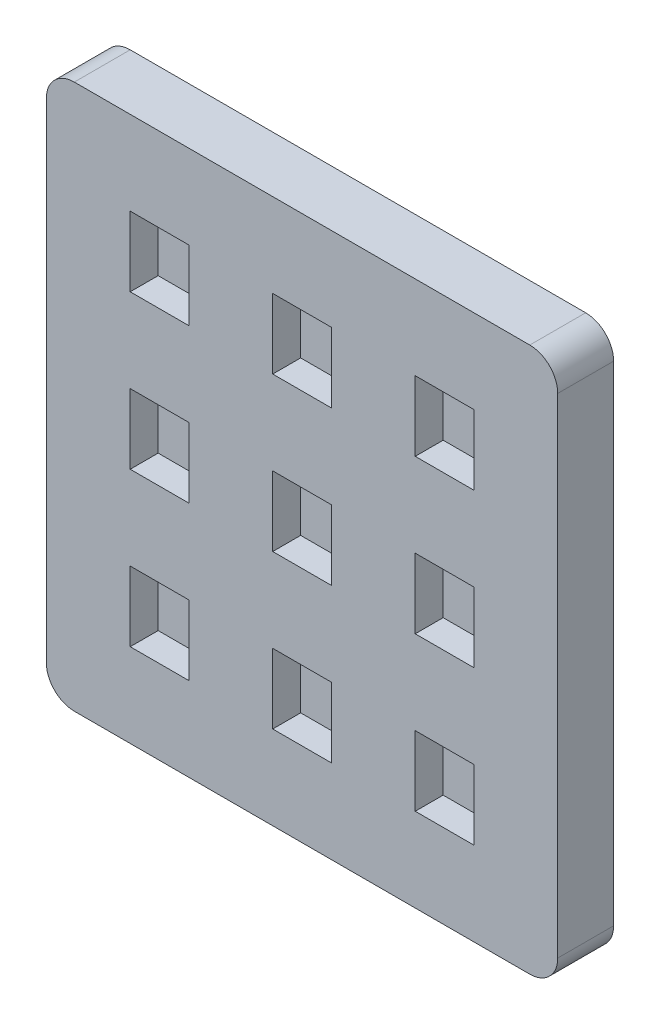
SolidWorks part; units mm, degrees
ref_plane "Front Plane" through (0, 0, 0) normal (0, 0, 1) x (1, 0, 0)
ref_plane "Top Plane" through (0, 0, 0) normal (0, 1, 0) x (1, 0, 0)
ref_plane "Right Plane" through (0, 0, 0) normal (1, 0, 0) x (0, 0, -1)
sketch "Sketch1" plane through (0, 0, 0) normal (0, 0, 1) x (1, 0, 0)
  line L1 (0, 0) -> (183, 0)
  line L2 (0, 0) -> (0, 195)
  line L3 (0, 195) -> (183, 195)
  line L4 (183, 0) -> (183, 195)
extrude "Boss-Extrude2" add sketch "Sketch1" along normal blind 20
sketch "Sketch3" plane through (0, 0, 20) normal (0, 0, 1) x (1, 0, 0)
  line L2 (30, 110) -> (51, 110)
  line L3 (30, 165) -> (51, 165)
  line L4 (51, 165) -> (51, 140)
  line L5 (51, 140) -> (30, 140)
  line L6 (30, 140) -> (30, 165)
  line L7 (51, 110) -> (51, 85)
  line L8 (51, 85) -> (30, 85)
  line L9 (30, 85) -> (30, 110)
  line L10 (81, 165) -> (81, 140)
  line L11 (30, 55) -> (51, 55)
  line L12 (51, 55) -> (51, 30)
  line L13 (51, 30) -> (30, 30)
  line L14 (30, 30) -> (30, 55)
  line L15 (81, 140) -> (102, 140)
  line L16 (102, 140) -> (102, 165)
  line L17 (102, 165) -> (81, 165)
  line L19 (81, 110) -> (81, 85)
  line L20 (81, 85) -> (102, 85)
  line L21 (102, 85) -> (102, 110)
  line L22 (102, 110) -> (81, 110)
  line L24 (81, 55) -> (81, 30)
  line L25 (81, 30) -> (102, 30)
  line L26 (102, 30) -> (102, 55)
  line L27 (102, 55) -> (81, 55)
  line L29 (132, 85) -> (132, 110)
  line L30 (132, 110) -> (153, 110)
  line L31 (153, 110) -> (153, 85)
  line L32 (153, 85) -> (132, 85)
  line L33 (132, 55) -> (132, 30)
  line L34 (132, 30) -> (153, 30)
  line L35 (153, 30) -> (153, 55)
  line L36 (153, 55) -> (132, 55)
  line L38 (132, 140) -> (153, 140)
  line L39 (153, 140) -> (153, 165)
  line L40 (153, 165) -> (132, 165)
  line L41 (132, 165) -> (132, 140)
extrude "Cut-Extrude1" cut sketch "Sketch3" against normal blind 10
sketch "Sketch4" plane through (0, 0, 20) normal (0, 0, 1) x (1, 0, 0)
  line L4 (0, 185) -> (0, 195)
  line L5 (0, 195) -> (10, 195)
  line L6 (173, 195) -> (183, 195)
  line L7 (183, 195) -> (183, 185)
  line L8 (183, 10) -> (183, 0)
  line L9 (183, 0) -> (173, 0)
  line L10 (10, 0) -> (0, 0)
  line L11 (0, 0) -> (0, 10)
  arc A0 (10, 195) -> (0, 185) centre (10, 185) ccw
  arc A1 (0, 10) -> (10, 0) centre (10, 10) ccw
  arc A2 (183, 10) -> (173, 0) centre (173, 10) cw
  arc A3 (183, 185) -> (173, 195) centre (173, 185) ccw
  point P10 (0, 195)
  point P13 (0, 0)
  point P16 (183, 0)
  point P19 (183, 195)
extrude "Cut-Extrude2" cut sketch "Sketch4" against normal blind 135
